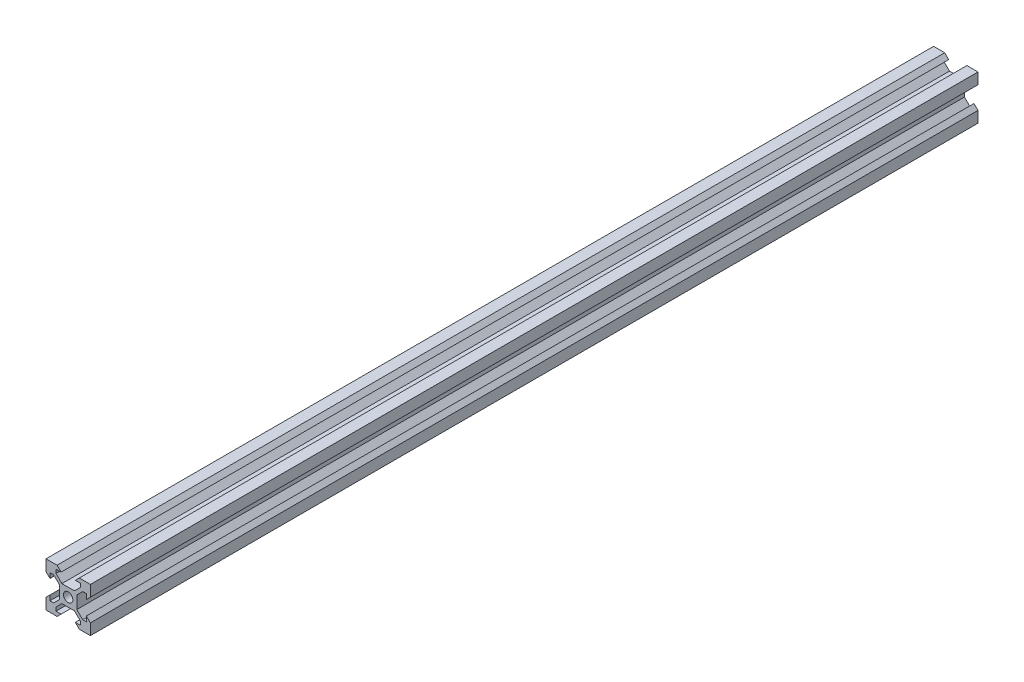
SolidWorks part; units mm, degrees
ref_plane "Front Plane" through (0, 0, 0) normal (0, 0, 1) x (1, 0, 0)
ref_plane "Top Plane" through (0, 0, 0) normal (0, 1, 0) x (1, 0, 0)
ref_plane "Right Plane" through (0, 0, 0) normal (1, 0, 0) x (0, 0, -1)
sketch "Sketch1" plane through (0, 0, 0) normal (0, 0, 1) x (1, 0, 0)
  line L0 (-10, 10) -> (-10, 5)
  line L1 (-10, 5) -> (-8.2, 3.2)
  line L2 (-8.2, 3.2) -> (-8.2, 5.4993)
  line L3 (-8.2, 5.4993) -> (-6.56, 5.4993)
  line L4 (-6.56, 5.4993) -> (-3.9007, 2.84)
  line L5 (-3.9007, 2.84) -> (-3.9007, -2.84)
  line L6 (-3.9007, -2.84) -> (-6.56, -5.4993)
  line L7 (-6.56, -5.4993) -> (-8.2, -5.4993)
  line L8 (-8.2, -5.4993) -> (-8.2, -3.2)
  line L9 (-8.2, -3.2) -> (-10, -5)
  line L10 (-10, -5) -> (-10, -10)
  line L11 (-10, -10) -> (-5, -10)
  line L12 (-5, -10) -> (-3.2, -8.2)
  line L13 (-3.2, -8.2) -> (-5.4993, -8.2)
  line L14 (-5.4993, -8.2) -> (-5.4993, -6.56)
  line L15 (-5.4993, -6.56) -> (-2.84, -3.9007)
  line L16 (-2.84, -3.9007) -> (2.84, -3.9007)
  line L17 (2.84, -3.9007) -> (5.4993, -6.56)
  line L18 (5.4993, -6.56) -> (5.4993, -8.2)
  line L19 (5.4993, -8.2) -> (3.2, -8.2)
  line L20 (3.2, -8.2) -> (5, -10)
  line L21 (5, -10) -> (10, -10)
  line L22 (10, -10) -> (10, -5)
  line L23 (10, -5) -> (8.2, -3.2)
  line L24 (8.2, -3.2) -> (8.2, -5.4993)
  line L25 (8.2, -5.4993) -> (6.56, -5.4993)
  line L26 (6.56, -5.4993) -> (3.9007, -2.84)
  line L27 (3.9007, -2.84) -> (3.9007, 2.84)
  line L28 (3.9007, 2.84) -> (6.56, 5.4993)
  line L29 (6.56, 5.4993) -> (8.2, 5.4993)
  line L30 (8.2, 5.4993) -> (8.2, 3.2)
  line L31 (8.2, 3.2) -> (10, 5)
  line L32 (10, 5) -> (10, 10)
  line L33 (10, 10) -> (5, 10)
  line L34 (5, 10) -> (3.2, 8.2)
  line L35 (3.2, 8.2) -> (5.4993, 8.2)
  line L36 (5.4993, 8.2) -> (5.4993, 6.56)
  line L37 (5.4993, 6.56) -> (2.84, 3.9007)
  line L38 (2.84, 3.9007) -> (-2.84, 3.9007)
  line L39 (-2.84, 3.9007) -> (-5.4993, 6.56)
  line L40 (-5.4993, 6.56) -> (-5.4993, 8.2)
  line L41 (-5.4993, 8.2) -> (-3.2, 8.2)
  line L42 (-3.2, 8.2) -> (-5, 10)
  line L43 (-5, 10) -> (-10, 10)
  circle A0 centre (0, 0) radius 2.1
extrude "Boss-Extrude1" add sketch "Sketch1" against normal blind 400
